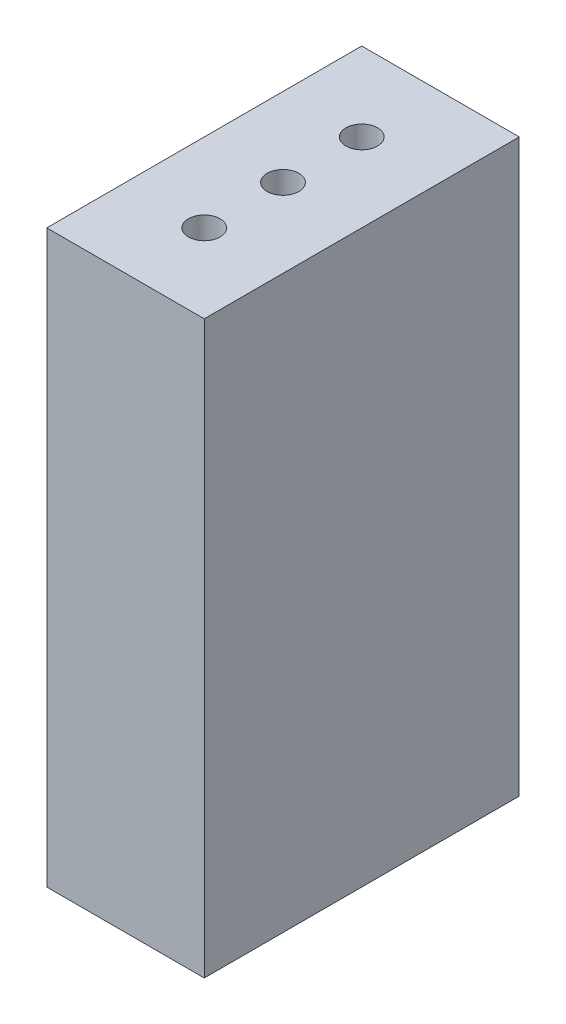
SolidWorks part; units mm, degrees
material "Cast Alloy Steel"
ref_plane "Front Plane" through (0, 0, 0) normal (0, 0, 1) x (1, 0, 0)
ref_plane "Top Plane" through (0, 0, 0) normal (0, 1, 0) x (1, 0, 0)
ref_plane "Right Plane" through (0, 0, 0) normal (1, 0, 0) x (0, 0, -1)
sketch "Sketch1" plane through (0, 0, 0) normal (0, 1, 0) x (1, 0, 0)
  line L1 (-12.7, 25.4) -> (12.7, 25.4)
  line L2 (-12.7, 25.4) -> (-12.7, -25.4)
  line L3 (-12.7, -25.4) -> (12.7, -25.4)
  line L4 (12.7, 25.4) -> (12.7, -25.4)
  line L5 (-12.7, 25.4) -> (12.7, -25.4) construction
  line L6 (-12.7, -25.4) -> (12.7, 25.4) construction
  point P0 (0, 0)
  dimension "D1" = 25.4
  dimension "D2" = 50.8
extrude "Boss-Extrude1" add sketch "Sketch1" along normal blind 92.075
sketch "Sketch2" plane through (0, 0, 25.4) normal (0, 0, 1) x (1, 0, 0)
  line L0 (0, 0) -> (0, 92.075) construction
  line L1 (-12.7, 0) -> (12.7, 0) construction
  line L2 (-12.7, 92.075) -> (12.7, 92.075) construction
  point P6 (0, 12.7)
  point P7 (0, 38.1)
  dimension "D1" = 12.7
  dimension "D2" = 25.4
hole_wizard "1/4-20 Tapped Hole1" positions "Sketch3" profile "Sketch4" tap size "1/4-20" standard "ANSI Inch"
sketch "Sketch3" plane through (0, 0, 25.4) normal (0, 0, 1) x (1, 0, 0)
  point P0 (0, 38.1)
  point P3 (0, 12.7)
sketch "Sketch4" plane through (0, 38.1, 25.4) normal (1, 0, 0) x (0, -1, 0)
  line L0 (0, 0) -> (0, 14.2338)
  line L1 (0, 14.2338) -> (2.5527, 12.7)
  line L2 (2.5527, 12.7) -> (2.5527, 0)
  line L5 (2.5527, 0) -> (0, 0)
  line L10 (0, 14.2338) -> (-2.5527, 12.7) construction
  line L11 (0, -6.35) -> (0, 107.95) construction
  dimension "Tap Drill Dia." = 5.1054
  dimension "Tap Drill Depth" = 12.7
  dimension "Drill Angle" = 118
sketch "Sketch5" plane through (0, 0, -25.4) normal (0, 0, -1) x (-1, 0, 0)
  line L4 (-12.7, 0) -> (12.7, 0)
  line L5 (12.7, 0) -> (12.7, 92.075)
  line L6 (12.7, 92.075) -> (-12.7, 92.075)
  line L7 (-12.7, 92.075) -> (-12.7, 0)
  line L8 (-12.7, 0) -> (12.7, 0)
  line L9 (12.7, 0) -> (12.7, 92.075)
  line L10 (12.7, 92.075) -> (-12.7, 92.075)
  line L11 (-12.7, 92.075) -> (-12.7, 0)
  point P2 (0, 12.7)
  point P4 (0, 38.1)
  dimension "D1" = 0
hole_wizard "1/4-20 Tapped Hole2" positions "Sketch6" profile "Sketch7" tap size "1/4-20" standard "ANSI Inch"
sketch "Sketch6" plane through (0, 0, -25.4) normal (0, 0, -1) x (-1, 0, 0)
  point P0 (0, 38.1)
  point P3 (0, 12.7)
sketch "Sketch7" plane through (0, 38.1, -25.4) normal (1, 0, 0) x (0, 1, 0)
  line L0 (0, 0) -> (0, 18.0438)
  line L1 (0, 18.0438) -> (2.5527, 16.51)
  line L2 (2.5527, 16.51) -> (2.5527, 0)
  line L5 (2.5527, 0) -> (0, 0)
  line L10 (0, 18.0438) -> (-2.5527, 16.51) construction
  line L11 (0, -6.35) -> (0, 107.95) construction
  dimension "Tap Drill Dia." = 5.1054
  dimension "Tap Drill Depth" = 16.51
  dimension "Drill Angle" = 118
sketch "Sketch8" plane through (0, 92.075, 0) normal (0, 1, 0) x (1, 0, 0)
  line L0 (0, -25.4) -> (0, 25.4)
  point P4 (0, 12.7)
  point P5 (0, 0)
  point P6 (0, -12.7)
  dimension "D1" = 12.7
  dimension "D2" = 12.7
hole_wizard "1/4-20 Tapped Hole3" positions "Sketch9" profile "Sketch10" tap size "1/4-20" standard "ANSI Inch"
sketch "Sketch9" plane through (0, 92.075, 0) normal (0, 1, 0) x (1, 0, 0)
  point P0 (0, 12.7)
  point P3 (0, 0)
  point P6 (0, -12.7)
sketch "Sketch10" plane through (0, 92.075, -12.7) normal (1, 0, 0) x (0, 0, 1)
  line L0 (0, 0) -> (0, 18.0438)
  line L1 (0, 18.0438) -> (2.5527, 16.51)
  line L2 (2.5527, 16.51) -> (2.5527, 0)
  line L5 (2.5527, 0) -> (0, 0)
  line L10 (0, 18.0438) -> (-2.5527, 16.51) construction
  line L11 (0, -6.35) -> (0, 107.95) construction
  dimension "Tap Drill Dia." = 5.1054
  dimension "Tap Drill Depth" = 16.51
  dimension "Drill Angle" = 118
